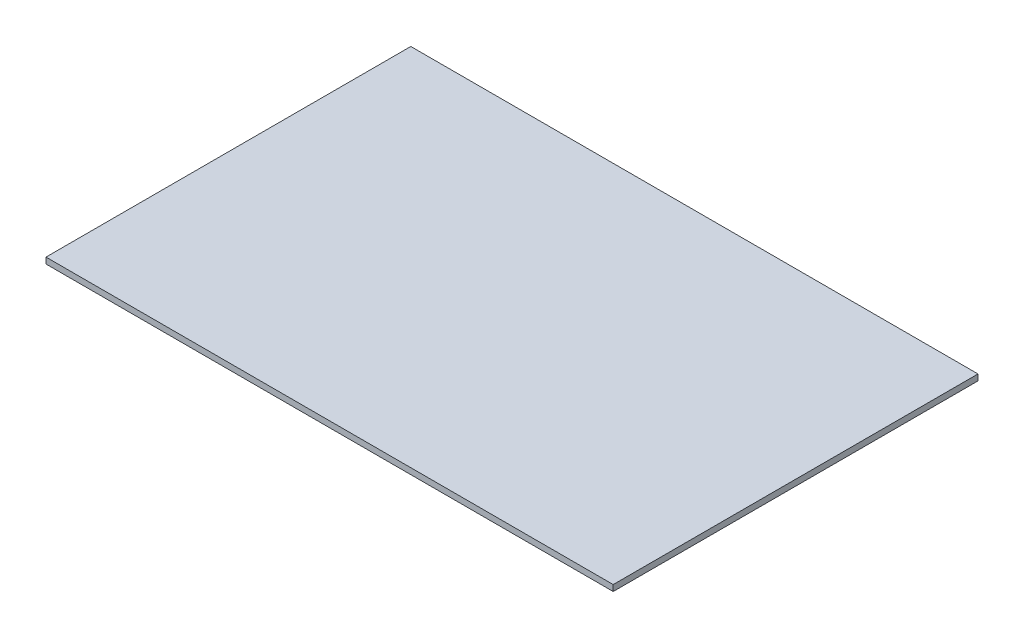
SolidWorks part; units mm, degrees
material "Pine"
ref_plane "Front Plane" through (0, 0, 0) normal (0, 0, 1) x (1, 0, 0)
ref_plane "Top Plane" through (0, 0, 0) normal (0, 1, 0) x (1, 0, 0)
ref_plane "Right Plane" through (0, 0, 0) normal (1, 0, 0) x (0, 0, -1)
sketch "Sketch1" plane through (0, 0, 0) normal (0, 1, 0) x (1, 0, 0)
  line L11 (-404.8125, 260.35) -> (404.8125, 260.35)
  line L22 (-404.8125, 260.35) -> (-404.8125, -260.35)
  line L23 (-404.8125, -260.35) -> (404.8125, -260.35)
  line L24 (404.8125, 260.35) -> (404.8125, -260.35)
  line L25 (-404.8125, 260.35) -> (404.8125, -260.35) construction
  line L26 (-404.8125, -260.35) -> (404.8125, 260.35) construction
  point P0 (0, 0)
  dimension "D1" = 809.625
  dimension "D2" = 520.7
extrude "Boss-Extrude1" add sketch "Sketch1" along normal blind 8.636
